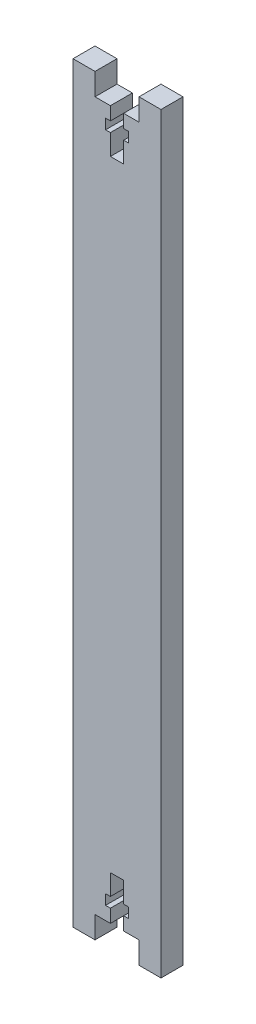
SolidWorks part; units mm, degrees
ref_plane "Front Plane" through (0, 0, 0) normal (0, 0, 1) x (1, 0, 0)
ref_plane "Top Plane" through (0, 0, 0) normal (0, 1, 0) x (1, 0, 0)
ref_plane "Right Plane" through (0, 0, 0) normal (1, 0, 0) x (0, 0, -1)
sketch "Sketch1" plane through (0, 0, 0) normal (0, 0, 1) x (1, 0, 0)
  line L0 (0, 166) -> (0, 5)
  line L5 (-20, 166) -> (-20, 5)
  line L6 (-10, 5) -> (-10, 16.2208) construction
  line L7 (-11.5, 5) -> (-15, 5)
  line L8 (-15, 0) -> (-20, 0)
  line L9 (-20, 0) -> (-20, 5)
  line L10 (-15, 0) -> (-15, 5)
  line L11 (-8.5, 5) -> (-5, 5)
  line L12 (-5, 5) -> (-5, 0)
  line L13 (-5, 0) -> (0, 0)
  line L14 (0, 0) -> (0, 5)
  line L15 (-10, 166) -> (-10, 154.7792) construction
  line L16 (-8.5, 166) -> (-5, 166)
  line L17 (-5, 171) -> (0, 171)
  line L18 (0, 171) -> (0, 166)
  line L19 (-5, 171) -> (-5, 166)
  line L20 (-11.5, 166) -> (-15, 166)
  line L21 (-15, 166) -> (-15, 171)
  line L22 (-15, 171) -> (-20, 171)
  line L23 (-20, 171) -> (-20, 166)
  line L24 (-8.5, 166) -> (-11.5, 166) construction
  line L25 (-11.5, 166) -> (-11.5, 163)
  line L26 (-11.5, 160.7) -> (-12.6, 160.7)
  line L27 (-7.4, 163) -> (-7.4, 160.7)
  line L28 (-12.6, 163) -> (-11.5, 163)
  line L29 (-11.5, 160.7) -> (-11.5, 156)
  line L30 (-11.5, 156) -> (-8.5, 156)
  line L31 (-8.5, 156) -> (-8.5, 160.7)
  line L32 (-8.5, 163) -> (-7.4, 163)
  line L33 (-12.6, 160.7) -> (-12.6, 163)
  line L34 (-7.4, 160.7) -> (-8.5, 160.7)
  line L35 (-8.5, 163) -> (-8.5, 166)
  line L36 (-10, 156) -> (-10, 166) construction
  line L37 (-11.5, 5) -> (-8.5, 5) construction
  line L38 (-8.5, 5) -> (-8.5, 8)
  line L39 (-8.5, 10.3) -> (-7.4, 10.3)
  line L40 (-12.6, 8) -> (-12.6, 10.3)
  line L41 (-7.4, 8) -> (-8.5, 8)
  line L42 (-8.5, 10.3) -> (-8.5, 15)
  line L43 (-8.5, 15) -> (-11.5, 15)
  line L44 (-11.5, 15) -> (-11.5, 10.3)
  line L45 (-11.5, 8) -> (-12.6, 8)
  line L46 (-7.4, 10.3) -> (-7.4, 8)
  line L47 (-12.6, 10.3) -> (-11.5, 10.3)
  line L48 (-11.5, 8) -> (-11.5, 5)
  line L49 (-10, 15) -> (-10, 5) construction
  point P4 (-17.5, 0)
  dimension "D1" = 10
  dimension "D2" = 5
  dimension "D3" = 5
  dimension "D4" = 10
  dimension "D5" = 5
  dimension "D6" = 5
  dimension "D7" = 5.2
  dimension "D8" = 3
  dimension "D9" = 2.3
  dimension "D10" = 3
  dimension "D11" = 10
  dimension "D12" = 5.2
  dimension "D13" = 3
  dimension "D14" = 2.3
  dimension "D15" = 3
  dimension "D16" = 10
  dimension "D17" = 171
extrude "Boss-Extrude1" add sketch "Sketch1" along normal blind 5
sketch "Sketch2" plane through (0, 0, 5) normal (0, 0, 1) x (1, 0, 0)
  line L0 (-9.9476, 274.152) -> (-9.9476, -26.6804) construction
  line L1 (0, 0) -> (0, 171) construction
  dimension "D1" = 9.9476
